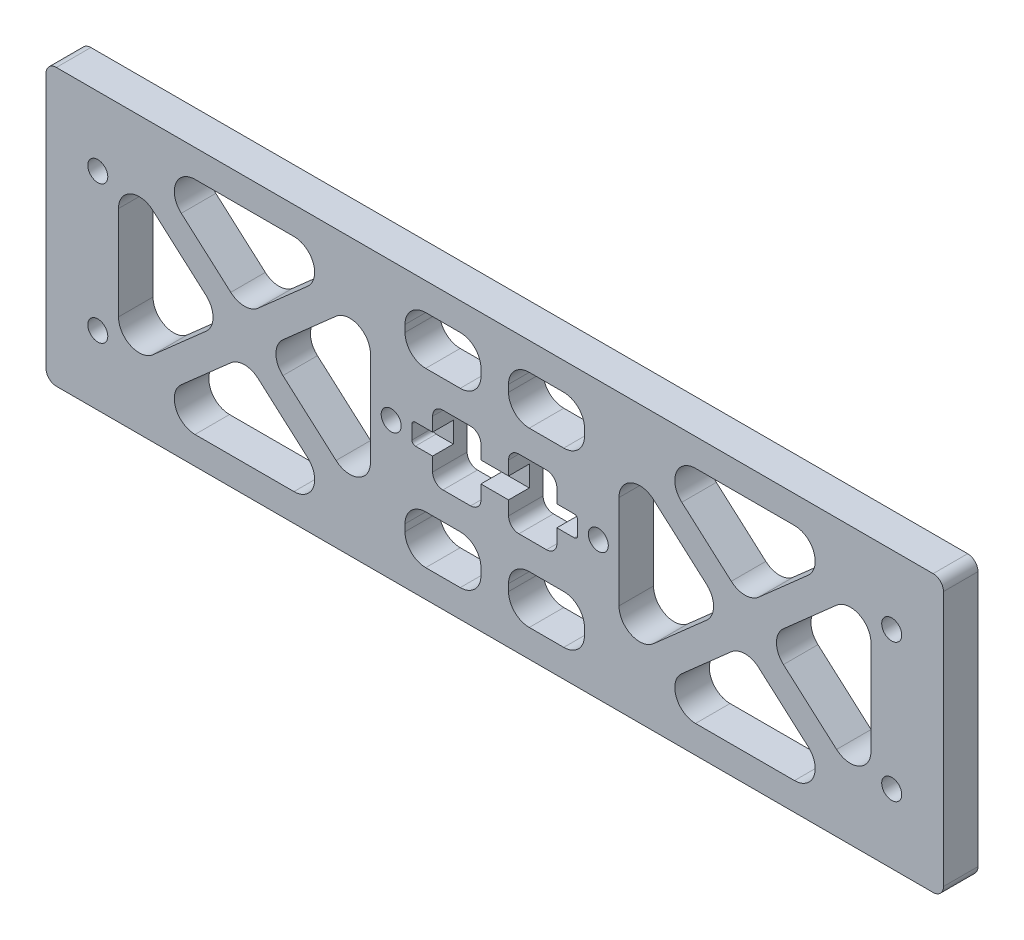
SolidWorks part; units mm, degrees
material "Thornel Mat VMA"
ref_plane "前视基准面" through (0, 0, 0) normal (0, 0, 1) x (1, 0, 0)
ref_plane "上视基准面" through (0, 0, 0) normal (0, 1, 0) x (1, 0, 0)
ref_plane "右视基准面" through (0, 0, 0) normal (1, 0, 0) x (0, 0, -1)
sketch "草图1" plane through (0, 0, 0) normal (0, 0, 1) x (1, 0, 0)
  line L0 (-57.5, 20) -> (-57.5, -20) construction
  line L1 (-65, -20) -> (65, -20)
  line L2 (-65, -20) -> (-65, 20)
  line L3 (-65, 20) -> (65, 20)
  line L4 (65, -20) -> (65, 20)
  line L5 (-65, -20) -> (65, 20) construction
  line L6 (-65, 20) -> (65, -20) construction
  line L7 (57.5, -20) -> (57.5, 20) construction
  line L8 (0, -1000) -> (0, 49000) construction
  line L9 (15, 0) -> (-15, 0) construction
  circle A0 centre (-57.5, -10) radius 1.45
  circle A1 centre (-57.5, 10) radius 1.45
  circle A2 centre (57.5, -10) radius 1.45
  circle A3 centre (57.5, 10) radius 1.45
  circle A4 centre (-15, 0) radius 1.45
  circle A5 centre (15, 0) radius 1.45
  point P0 (0, 0)
  point P23 (0, 0)
  dimension "D5" = 2.9
  dimension "D6" = 20
  dimension "D7" = 10
  dimension "D9" = 2.9
  dimension "D1" = 130
  dimension "D2" = 7.5
  dimension "D3" = 7.5
  dimension "D4" = 40
  dimension "D8" = 30
extrude "凸台-拉伸1" add sketch "草图1" along normal blind 5
sketch "草图3" plane through (0, 0, 5) normal (0, 0, 1) x (1, 0, 0)
  line L1 (-12, -1.5) -> (12, -1.5)
  line L2 (-12, -1.5) -> (-12, 1.5)
  line L3 (-12, 1.5) -> (12, 1.5)
  line L4 (12, -1.5) -> (12, 1.5)
  line L5 (-12, -1.5) -> (12, 1.5) construction
  line L6 (-12, 1.5) -> (12, -1.5) construction
  point P0 (0, 0)
  dimension "D1" = 3
  dimension "D2" = 24
extrude "切除-拉伸1" cut sketch "草图3" against normal blind 3
sketch "草图4" plane through (0, 0, 5) normal (0, 0, 1) x (1, 0, 0)
  line L0 (0, -1000) -> (0, 49000) construction
  line L1 (-9, -5) -> (-2, -5)
  line L2 (-9, -5) -> (-9, 5)
  line L3 (-9, 5) -> (-2, 5)
  line L4 (-2, -5) -> (-2, 5)
  line L5 (-9, -5) -> (-2, 5) construction
  line L6 (-9, 5) -> (-2, -5) construction
  line L7 (9, 5) -> (2, -5) construction
  line L8 (9, -5) -> (2, 5) construction
  line L9 (2, -5) -> (2, 5)
  line L10 (9, 5) -> (2, 5)
  line L11 (9, -5) -> (9, 5)
  line L12 (9, -5) -> (2, -5)
  point P0 (-5.5, 0)
  point P13 (5.5, 0)
  dimension "D1" = 7
  dimension "D2" = 10
  dimension "D3" = 5.5
extrude "切除-拉伸2" cut sketch "草图4" against normal through all
sketch "草图5" plane through (0, 0, 5) normal (0, 0, 1) x (1, 0, 0)
  line L0 (65, 20) -> (-65, 20) construction
  line L1 (-55.5, -17) -> (-17, -17) construction
  line L2 (-55.5, -17) -> (-55.5, 17) construction
  line L3 (-55.5, 17) -> (-17, 17) construction
  line L4 (-17, -17) -> (-17, 17) construction
  line L5 (-55.5, -17) -> (-17, 17) construction
  line L6 (-55.5, 17) -> (-17, -17) construction
  line L7 (-65, -20) -> (65, -20) construction
  line L8 (-51.3462, 16) -> (-36.25, 2.6683)
  line L9 (-36.25, 2.6683) -> (-21.1538, 16)
  line L10 (-21.1538, 16) -> (-51.3462, 16)
  line L11 (-54.5, 13.4486) -> (-39.2714, 0)
  line L12 (-39.2714, 0) -> (-54.5, -13.4486)
  line L13 (-54.5, -13.4486) -> (-54.5, 13.4486)
  line L14 (-18, 13.4486) -> (-18, -13.4486)
  line L15 (-18, -13.4486) -> (-33.2286, 0)
  line L16 (-33.2286, 0) -> (-18, 13.4486)
  line L17 (-51.3462, -16) -> (-21.1538, -16)
  line L18 (-21.1538, -16) -> (-36.25, -2.6683)
  line L19 (-36.25, -2.6683) -> (-51.3462, -16)
  line L20 (0, -1000) -> (0, 49000) construction
  line L21 (-2, 5) -> (-9, 5) construction
  line L22 (-13, 9) -> (-2, 9)
  line L23 (-13, 9) -> (-13, 16)
  line L24 (-13, 16) -> (-2, 16)
  line L25 (-2, 9) -> (-2, 16)
  line L26 (-13, 9) -> (-2, 16) construction
  line L27 (-13, 16) -> (-2, 9) construction
  line L28 (-1000, 0) -> (49000, 0) construction
  line L29 (-13, -16) -> (-2, -16)
  line L30 (-2, -9) -> (-2, -16)
  line L31 (-13, -9) -> (-2, -9)
  line L32 (-13, -9) -> (-13, -16)
  line L33 (13, 16) -> (2, 9) construction
  line L34 (13, 9) -> (2, 16) construction
  line L35 (55.5, 17) -> (17, -17) construction
  line L36 (55.5, -17) -> (17, 17) construction
  line L37 (17, -17) -> (17, 17) construction
  line L38 (55.5, 17) -> (17, 17) construction
  line L39 (55.5, -17) -> (55.5, 17) construction
  line L40 (55.5, -17) -> (17, -17) construction
  line L41 (13, -9) -> (13, -16)
  line L42 (13, -9) -> (2, -9)
  line L43 (2, -9) -> (2, -16)
  line L44 (13, -16) -> (2, -16)
  line L45 (2, 9) -> (2, 16)
  line L46 (13, 16) -> (2, 16)
  line L47 (13, 9) -> (13, 16)
  line L48 (13, 9) -> (2, 9)
  line L49 (36.25, -2.6683) -> (51.3462, -16)
  line L50 (21.1538, -16) -> (36.25, -2.6683)
  line L51 (51.3462, -16) -> (21.1538, -16)
  line L52 (33.2286, 0) -> (18, 13.4486)
  line L53 (18, -13.4486) -> (33.2286, 0)
  line L54 (18, 13.4486) -> (18, -13.4486)
  line L55 (54.5, -13.4486) -> (54.5, 13.4486)
  line L56 (39.2714, 0) -> (54.5, -13.4486)
  line L57 (54.5, 13.4486) -> (39.2714, 0)
  line L58 (21.1538, 16) -> (51.3462, 16)
  line L59 (36.25, 2.6683) -> (21.1538, 16)
  line L60 (51.3462, 16) -> (36.25, 2.6683)
  circle A0 centre (-57.5, 10) radius 1.45 construction
  circle A1 centre (-15, 0) radius 1.45 construction
  point P0 (-36.25, 0)
  point P18 (-55.5, 0)
  point P20 (-7.5, 12.5)
  point P66 (7.5, 12.5)
  point P67 (36.25, 0)
  dimension "D4" = 2
  dimension "D1" = 3
  dimension "D2" = 3
  dimension "D3" = 2
  dimension "D5" = 1
  dimension "D6" = 1
  dimension "D7" = 2
  dimension "D8" = 2
  dimension "D9" = 2
  dimension "D10" = 2
  dimension "D12" = 4
  dimension "D13" = 5
  dimension "D14" = 4
  dimension "D15" = 2
  dimension "D11" = 2
extrude "切除-拉伸3" cut sketch "草图5" against normal through all
fillet "圆角1" radius 3 40 edges at (-54.5, 13.4486, 2.5) (-54.5, -13.4486, 2.5) (18, -13.4486, 2.5) (18, 13.4486, 2.5) (33.2286, 0, 2.5) (39.2714, 0, 2.5) (54.5, 13.4486, 2.5) (54.5, -13.4486, 2.5) (21.1538, 16, 2.5) (51.3462, 16, 2.5) (36.25, 2.6683, 2.5) (-33.2286, 0, 2.5) (-18, 13.4486, 2.5) (-18, -13.4486, 2.5) (-36.25, -2.6683, 2.5) (-21.1538, -16, 2.5) (-51.3462, -16, 2.5) (-2, 9, 2.5) (-13, 9, 2.5) (-13, 16, 2.5) (-2, 16, 2.5) (-21.1538, 16, 2.5) (-36.25, 2.6683, 2.5) (-51.3462, 16, 2.5) (36.25, -2.6683, 2.5) (51.3462, -16, 2.5) (21.1538, -16, 2.5) (13, -9, 2.5) (13, -16, 2.5) (2, -16, 2.5) (2, -9, 2.5) (13, 9, 2.5) (2, 9, 2.5) (2, 16, 2.5) (13, 16, 2.5) (-13, -9, 2.5) (-2, -9, 2.5) (-2, -16, 2.5) (-13, -16, 2.5) (-39.2714, 0, 2.5)
fillet "圆角2" radius 1.5 8 edges at (9, -5, 2.5) (2, -5, 2.5) (9, 5, 2.5) (2, 5, 2.5) (-2, -5, 2.5) (-9, -5, 2.5) (-2, 5, 2.5) (-9, 5, 2.5)
fillet "圆角3" radius 1.5 4 edges at (65, -20, 2.5) (-65, 20, 2.5) (65, 20, 2.5) (-65, -20, 2.5)
fillet "圆角4" radius 0.5 4 edges at (12, -1.5, 3.5) (12, 1.5, 3.5) (-12, -1.5, 3.5) (-12, 1.5, 3.5)
